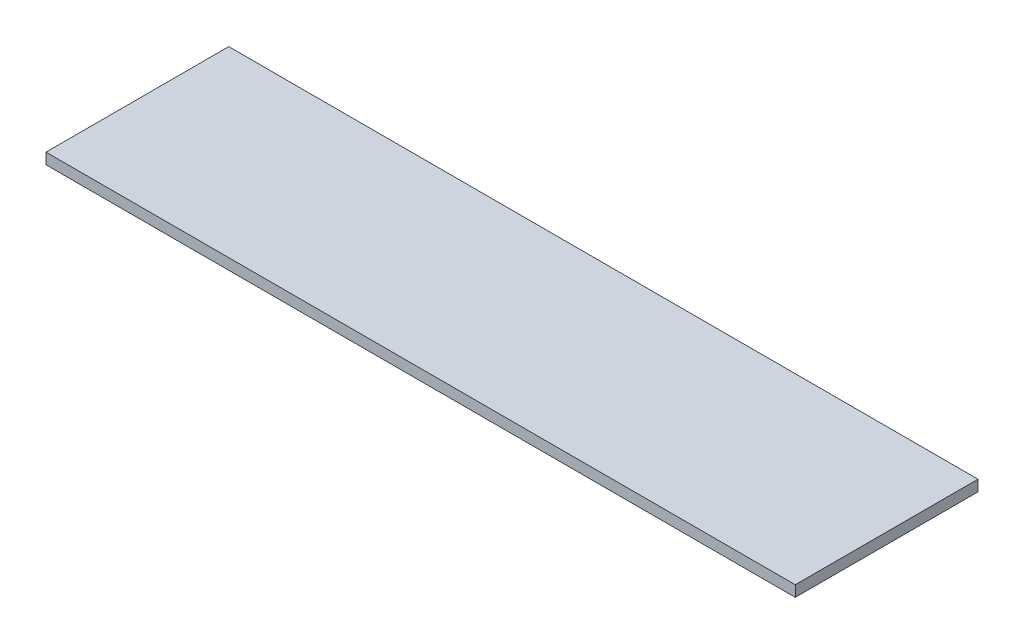
SolidWorks part; units mm, degrees
ref_plane "Plano frontal" through (0, 0, 0) normal (0, 0, 1) x (1, 0, 0)
ref_plane "Plano superior" through (0, 0, 0) normal (0, 1, 0) x (1, 0, 0)
ref_plane "Plano direito" through (0, 0, 0) normal (1, 0, 0) x (0, 0, -1)
sketch "Esboço2" plane through (0, 0, 0) normal (0, 1, 0) x (1, 0, 0)
  line L0 (0, 0) -> (120, 0)
  line L1 (0, 0) -> (0, 100)
  line L2 (120, 0) -> (120, 100)
  line L3 (0, 100) -> (120, 100)
  dimension "D1" = 100
  dimension "D2" = 120
extrude "Ressalto-extrusão1" add sketch "Esboço2" along normal blind 6
sketch "Esboço3" plane through (0, 0, 0) normal (-1, 0, 0) x (0, 0, 1)
  line L1 (-100, 6) -> (0, 6)
  line L2 (-100, 6) -> (-100, 0)
  line L3 (-100, 0) -> (0, 0)
  line L4 (0, 6) -> (0, 0)
extrude "Ressalto-extrusão3" add sketch "Esboço3" along normal blind 70
sketch "Esboço4" plane through (120, 0, 0) normal (1, 0, 0) x (0, 0, -1)
  line L1 (0, 6) -> (100, 6)
  line L2 (0, 6) -> (0, 0)
  line L3 (0, 0) -> (100, 0)
  line L4 (100, 6) -> (100, 0)
extrude "Ressalto-extrusão4" add sketch "Esboço4" along normal blind 120
sketch "Esboço5" plane through (240, 0, 0) normal (1, 0, 0) x (0, 0, -1)
  line L1 (0, 6) -> (100, 6)
  line L2 (0, 6) -> (0, 0)
  line L3 (0, 0) -> (100, 0)
  line L4 (100, 6) -> (100, 0)
extrude "Ressalto-extrusão5" add sketch "Esboço5" along normal blind 100
